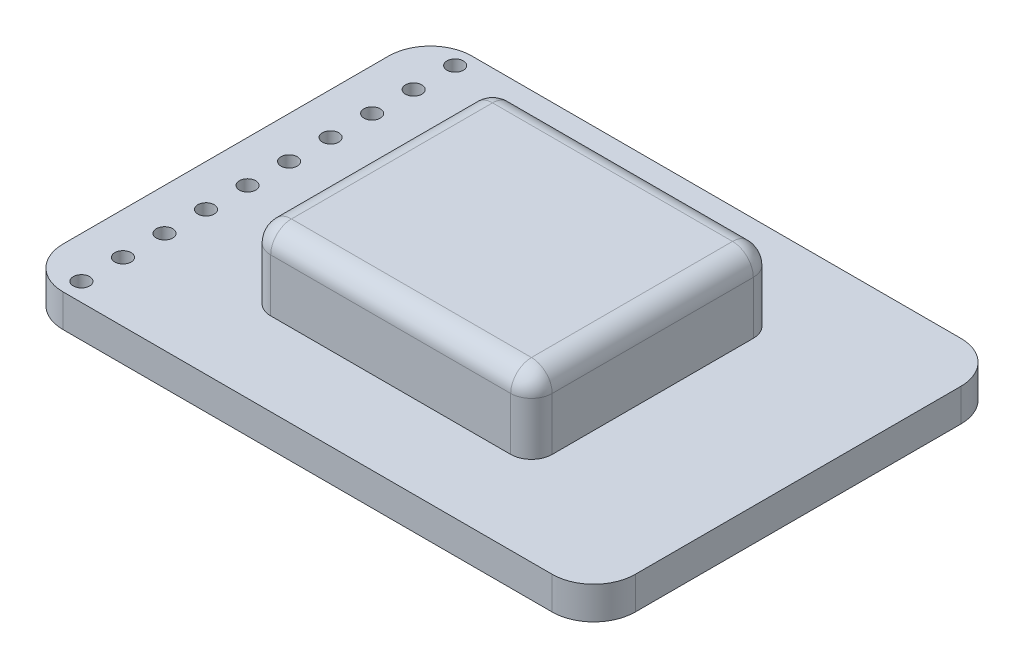
SolidWorks part; units mm, degrees
ref_plane "Front Plane" through (0, 0, 0) normal (0, 0, 1) x (1, 0, 0)
ref_plane "Top Plane" through (0, 0, 0) normal (0, 1, 0) x (1, 0, 0)
ref_plane "Right Plane" through (0, 0, 0) normal (1, 0, 0) x (0, 0, -1)
sketch "Sketch1" plane through (0, 0, 0) normal (0, 1, 0) x (1, 0, 0)
  line L1 (0, 0) -> (35, 0)
  line L2 (0, 0) -> (0, 25)
  line L3 (0, 25) -> (35, 25)
  line L4 (35, 0) -> (35, 25)
  dimension "D1" = 35
  dimension "D2" = 25
extrude "Boss-Extrude1" add sketch "Sketch1" along normal blind 2
fillet "Fillet1" radius 2.54 4 edges at (0, 1, -25) (35, 1, -25) (35, 1, 0) (0, 1, 0)
sketch "Sketch2" plane through (0, 2, 0) normal (0, 1, 0) x (1, 0, 0)
  line L0 (32.46, 25) -> (2.54, 25) construction
  line L1 (8.89, 19.92) -> (26.11, 19.92)
  line L2 (8.89, 19.92) -> (8.89, 5.08)
  line L3 (8.89, 5.08) -> (26.11, 5.08)
  line L4 (26.11, 19.92) -> (26.11, 5.08)
  line L5 (2.54, 0) -> (32.46, 0) construction
  line L6 (35, 2.54) -> (35, 22.46) construction
  line L7 (0, 22.46) -> (0, 2.54) construction
  dimension "D1" = 5.08
  dimension "D2" = 5.08
  dimension "D3" = 8.89
  dimension "D4" = 8.89
extrude "Boss-Extrude2" add sketch "Sketch2" along normal blind 4.5
fillet "Fillet2" radius 1.27 8 edges at (26.11, 4.25, -19.92) (8.89, 4.25, -19.92) (8.89, 4.25, -5.08) (26.11, 4.25, -5.08) (17.5, 6.5, -19.92) (26.11, 6.5, -12.5) (8.89, 6.5, -12.5) (17.5, 6.5, -5.08)
sketch "Sketch3" plane through (0, 2, 0) normal (0, 1, 0) x (1, 0, 0)
  line L0 (32.46, 25) -> (2.54, 25) construction
  line L1 (0, 22.46) -> (0, 2.54) construction
  circle A0 centre (2.54, 23.984) radius 0.5
  circle A1 centre (2.54, 21.444) radius 0.5
  circle A2 centre (2.54, 18.904) radius 0.5
  circle A3 centre (2.54, 16.364) radius 0.5
  circle A4 centre (2.54, 13.824) radius 0.5
  circle A5 centre (2.54, 11.284) radius 0.5
  circle A6 centre (2.54, 8.744) radius 0.5
  circle A7 centre (2.54, 6.204) radius 0.5
  circle A8 centre (2.54, 3.664) radius 0.5
  circle A9 centre (2.54, 1.124) radius 0.5
  dimension "D1" = 10
  dimension "D2" = 1.016
  dimension "D3" = 2.54
extrude "Cut-Extrude1" cut sketch "Sketch3" against normal blind 4.5
